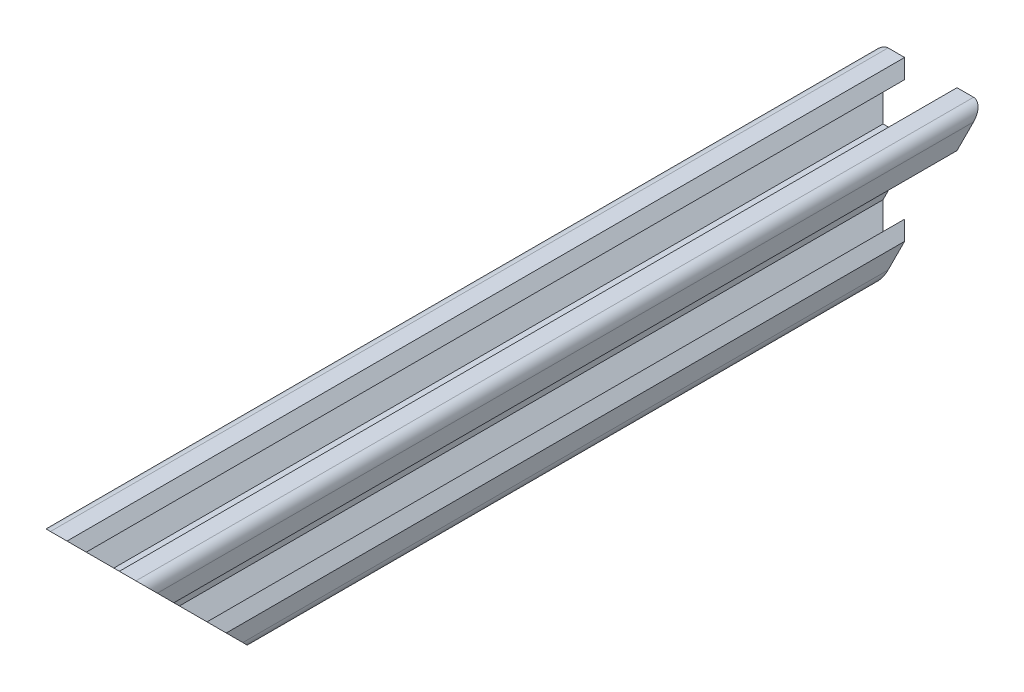
SolidWorks part; units mm, degrees
material "6061 Alloy"
ref_plane "Front Plane" through (0, 0, 0) normal (0, 0, 1) x (1, 0, 0)
ref_plane "Top Plane" through (0, 0, 0) normal (0, 1, 0) x (1, 0, 0)
ref_plane "Right Plane" through (0, 0, 0) normal (1, 0, 0) x (0, 0, -1)
sketch "Sketch1" plane through (0, 0, 0) normal (0, 0, 1) x (1, 0, 0)
  line L0 (-4.9, -10) -> (-5.5, -10)
  line L1 (-10, -10) -> (10, -10) construction
  line L2 (-10, -10) -> (-10, 10) construction
  line L3 (-10, 10) -> (10, 10) construction
  line L4 (10, -10) -> (10, 10) construction
  line L5 (-10, -10) -> (10, 10) construction
  line L6 (-10, 10) -> (10, -10) construction
  line L7 (-3.6, 3.6) -> (3.6, 3.6)
  line L8 (-3.6, 3.6) -> (-3.6, -3.6)
  line L9 (-3.6, -3.6) -> (3.6, -3.6)
  line L10 (3.6, 3.6) -> (3.6, -3.6)
  line L11 (-8, 10) -> (-5.5, 10)
  line L12 (-10, 8) -> (-10, 5.5)
  line L13 (-10, 5.5) -> (-5.5, 5.5)
  line L14 (-5.5, 10) -> (-5.5, 5.5)
  line L15 (8, 10) -> (5.5, 10)
  line L16 (10, 8) -> (10, 5.5)
  line L17 (10, 5.5) -> (5.5, 5.5)
  line L18 (5.5, 10) -> (5.5, 5.5)
  line L19 (8, -10) -> (5.5, -10)
  line L20 (10, -8) -> (10, -5.5)
  line L21 (10, -5.5) -> (5.5, -5.5)
  line L22 (5.5, -10) -> (5.5, -5.5)
  line L23 (-8, -10) -> (-5.5, -10)
  line L24 (-10, -8) -> (-10, -5.5)
  line L25 (-10, -5.5) -> (-5.5, -5.5)
  line L26 (-5.5, -10) -> (-5.5, -5.5)
  line L27 (-3.1, -8.2) -> (-4.9, -10)
  line L28 (-3.1, -8.2) -> (-5.5, -8.2)
  line L29 (4.9, -10) -> (5.5, -10)
  line L30 (3.1, -8.2) -> (4.9, -10)
  line L31 (3.1, -8.2) -> (5.5, -8.2)
  line L32 (-4.9, 10) -> (-5.5, 10)
  line L33 (-3.1, 8.2) -> (-4.9, 10)
  line L34 (-3.1, 8.2) -> (-5.5, 8.2)
  line L35 (4.9, 10) -> (5.5, 10)
  line L36 (0, 0) -> (17.4618, 0) construction
  line L37 (3.1, 8.2) -> (4.9, 10)
  line L38 (3.1, 8.2) -> (5.5, 8.2)
  line L39 (8.2, 3.1) -> (8.2, 5.5)
  line L40 (8.2, 3.1) -> (10, 4.9)
  line L41 (10, 4.9) -> (10, 5.5)
  line L42 (10, -4.9) -> (10, -5.5)
  line L43 (8.2, -3.1) -> (10, -4.9)
  line L44 (8.2, -3.1) -> (8.2, -5.5)
  line L57 (-8.2, -3.1) -> (-10, -4.9)
  line L58 (-10, -4.9) -> (-10, -5.5)
  line L61 (-8.2, -3.1) -> (-8.2, -5.5)
  line L62 (-8.2, 3.1) -> (-10, 4.9)
  line L63 (-10, 4.9) -> (-10, 5.5)
  line L66 (-8.2, 3.1) -> (-8.2, 5.5)
  line L67 (-2.7729, 2.7729) -> (-6.4508, 6.4508) construction
  line L68 (-2.2426, 3.3033) -> (-5.9205, 6.9812)
  line L69 (-3.3033, 2.2426) -> (-6.9812, 5.9205)
  line L70 (6.7372, 6.7372) -> (2.7729, 2.7729)
  line L71 (6.309, -6.309) -> (2.7729, -2.7729)
  line L72 (-2.8687, -2.8687) -> (-6.5971, -6.5971)
  line L73 (6.2069, 7.2675) -> (2.2426, 3.3033)
  line L74 (6.8393, -5.7786) -> (3.3033, -2.2426)
  line L75 (-3.399, -2.3384) -> (-7.1274, -6.0667)
  line L76 (7.2675, 6.2069) -> (3.3033, 2.2426)
  line L77 (5.7786, -6.8393) -> (2.2426, -3.3033)
  line L78 (-2.3384, -3.399) -> (-6.0667, -7.1274)
  circle A0 centre (0, 0) radius 2.1
  arc A1 (-8, -10) -> (-10, -8) centre (-8, -8) cw
  arc A2 (8, -10) -> (10, -8) centre (8, -8) ccw
  arc A3 (8, 10) -> (10, 8) centre (8, 8) cw
  arc A4 (-8, 10) -> (-10, 8) centre (-8, 8) ccw
  point P0 (0, 0)
  dimension "D3" = 4.2
  dimension "D12" = 2
  dimension "D1" = 20
  dimension "D4" = 6.4
  dimension "D5" = 6.4
  dimension "D6" = 6.4
  dimension "D7" = 6.4
  dimension "D8" = 4.5
  dimension "D9" = 4.5
  dimension "D10" = 4.5
  dimension "D11" = 4.5
  dimension "D13" = 45
  dimension "D19" = 45
  dimension "D20" = 6.2
  dimension "D23" = 1.8
  dimension "D24" = 1.8
  dimension "D28" = 0.75
  dimension "D26" = 0.75
  dimension "D27" = 0.75
  dimension "D29" = 0.75
extrude "Boss-Extrude1" add sketch "Sketch1" along normal blind 156.74
sketch "Sketch2" plane through (10, 0, 0) normal (1, 0, 0) x (0, 0, -1)
  line L0 (-156.74, 10) -> (-136.74, -10)
  line L1 (-156.74, -10) -> (0, -10) construction
  line L2 (-156.74, 10) -> (0, 10) construction
  line L4 (0, 10) -> (-20, -10)
  line L6 (-156.74, 10) -> (-156.74, -10)
  line L7 (-156.74, -10) -> (-136.74, -10)
  line L8 (0, 10) -> (0, -10)
  line L9 (0, -10) -> (-20, -10)
  dimension "D1" = 45
extrude "Cut-Extrude1" cut sketch "Sketch2" against normal through all
